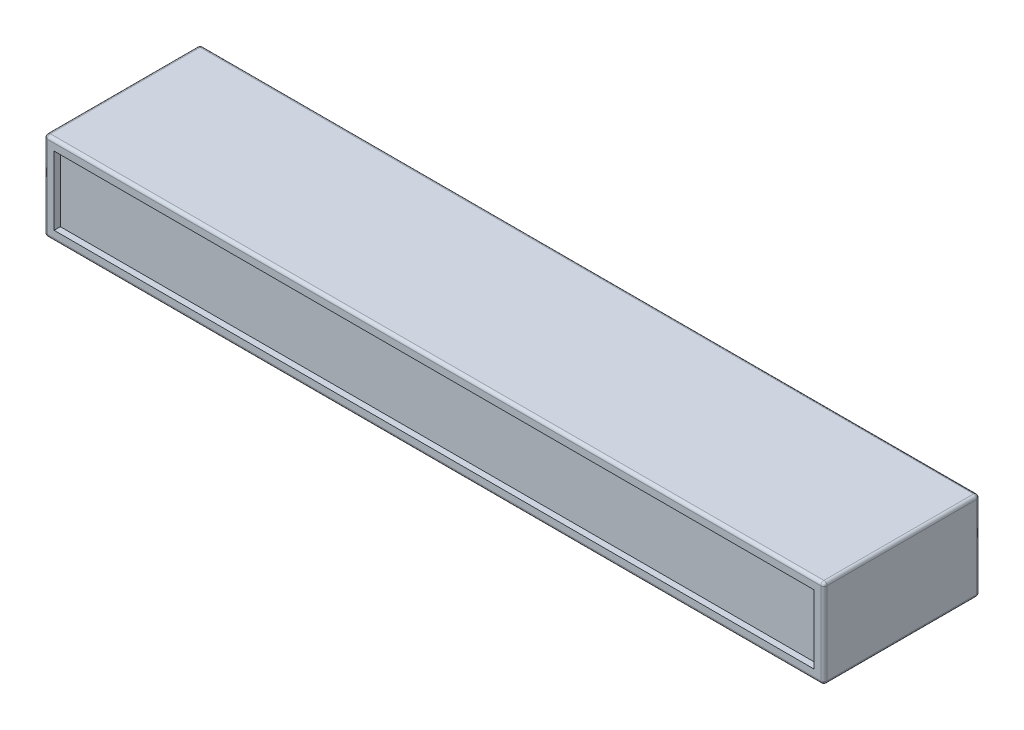
SolidWorks part; units mm, degrees
ref_plane "Front Plane" through (0, 0, 0) normal (0, 0, 1) x (1, 0, 0)
ref_plane "Top Plane" through (0, 0, 0) normal (0, 1, 0) x (1, 0, 0)
ref_plane "Right Plane" through (0, 0, 0) normal (1, 0, 0) x (0, 0, -1)
sketch "Sketch1" plane through (0, 0, 0) normal (0, 0, 1) x (1, 0, 0)
  line L1 (0, 0) -> (2500, 0)
  line L2 (0, 0) -> (0, 284)
  line L3 (0, 284) -> (2500, 284)
  line L4 (2500, 0) -> (2500, 284)
  dimension "D1" = 284
  dimension "D2" = 2500
extrude "Boss-Extrude1" add sketch "Sketch1" along normal blind 500
fillet "Fillet1" radius 10 12 edges at (2500, 142, 0) (2500, 0, 250) (1250, 0, 0) (2500, 284, 250) (1250, 284, 0) (0, 284, 250) (0, 0, 250) (0, 142, 0) (1250, 284, 500) (2500, 142, 500) (1250, 0, 500) (0, 142, 500)
sketch "Sketch2" plane through (0, 0, 500) normal (0, 0, 1) x (1, 0, 0)
  line L0 (2490, 0) -> (10, 0) construction
  line L1 (2468, 252) -> (32, 252)
  line L2 (2468, 252) -> (2468, 32)
  line L3 (2468, 32) -> (32, 32)
  line L4 (32, 252) -> (32, 32)
  line L5 (10, 284) -> (2490, 284) construction
  line L6 (2500, 274) -> (2500, 10) construction
  line L7 (0, 10) -> (0, 274) construction
  dimension "D1" = 32
  dimension "D2" = 32
  dimension "D3" = 32
  dimension "D4" = 32
extrude "Cut-Extrude1" cut sketch "Sketch2" against normal blind 20
